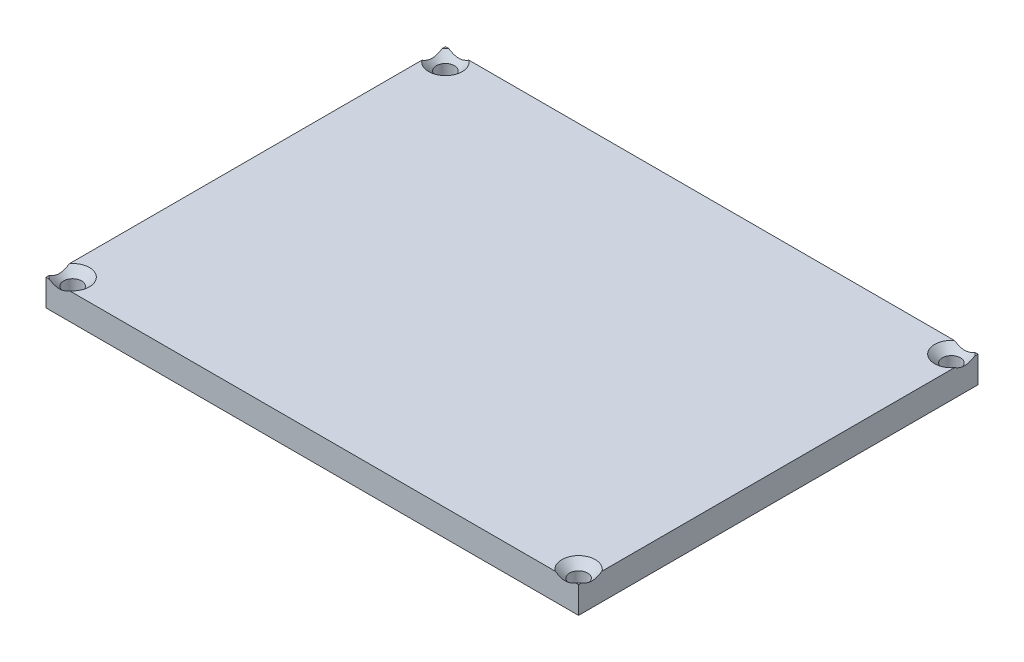
SolidWorks part; units mm, degrees
ref_plane "Alzado" through (0, 0, 0) normal (0, 0, 1) x (1, 0, 0)
ref_plane "Planta" through (0, 0, 0) normal (0, 1, 0) x (1, 0, 0)
ref_plane "Vista lateral" through (0, 0, 0) normal (1, 0, 0) x (0, 0, -1)
sketch "Croquis1" plane through (0, 0, 0) normal (0, 1, 0) x (1, 0, 0)
  line L1 (-67.5839, 18.7136) -> (32.4161, 18.7136)
  line L2 (-67.5839, 18.7136) -> (-67.5839, -56.2864)
  line L3 (-67.5839, -56.2864) -> (32.4161, -56.2864)
  line L4 (32.4161, 18.7136) -> (32.4161, -56.2864)
  dimension "D1" = 100
  dimension "D2" = 75
extrude "Saliente-Extruir1" add sketch "Croquis1" along normal blind 5
sketch "Croquis2" plane through (0, 0, 0) normal (0, 1, 0) x (1, 0, 0)
  line L0 (-67.5839, 18.7136) -> (-67.5839, -56.2864) construction
  line L1 (32.4161, 18.7136) -> (-67.5839, 18.7136) construction
  line L2 (32.4161, -56.2864) -> (32.4161, 18.7136) construction
  line L3 (-67.5839, -56.2864) -> (32.4161, -56.2864) construction
  point P0 (-65.0839, 16.2136)
  point P1 (29.9161, 16.2136)
  point P2 (29.9161, -53.7864)
  point P3 (-65.0839, -53.7864)
  dimension "D1" = 2.5
  dimension "D2" = 2.5
  dimension "D3" = 2.5
  dimension "D4" = 2.5
  dimension "D5" = 2.5
  dimension "D6" = 2.5
  dimension "D7" = 2.5
  dimension "D8" = 2.5
hole_wizard "Avellanado para tornillo con cabeza plana avellanada de M31" positions "Croquis3D1" profile "Croquis3" countersink size "M3" standard "DIN"
sketch3d "Croquis3D1"
  line L0 (-67.5839, 5, -18.7136) -> (-67.5839, 5, 56.2864) construction
  line L1 (-67.5839, 5, 56.2864) -> (32.4161, 5, 56.2864) construction
  point P0 (-65.0839, 0, -16.2136)
  point P3 (29.9161, 0, -16.2136)
  point P6 (29.9161, 0, 53.7864)
  point P9 (-65.0839, 0, 53.7864)
  point P12 (-65.0839, 5, -16.2136)
  point P15 (29.9161, 5, -16.2136)
  point P17 (29.9161, 5, 53.7864)
  point P19 (-65.0839, 5, 53.7864)
  dimension "D1" = 2.5
  dimension "D2" = 2.5
  dimension "D3" = 2.5
  dimension "D4" = 2.5
sketch "Croquis3" plane through (-65.0839, 5, 53.7864) normal (1, 0, 0) x (0, 0, 1)
  line L0 (0, 0) -> (0, 5)
  line L1 (0, 5) -> (1.7, 5)
  line L2 (1.7, 5) -> (1.7, 1.45)
  line L3 (1.7, 1.45) -> (3.15, 0)
  line L5 (3.15, 0) -> (0, 0)
  line L6 (-1.7, 1.45) -> (-3.15, 0) construction
  line L11 (0, -6.35) -> (0, 107.95) construction
  dimension "Diámetro de taladro hasta el siguiente" = 3.4
  dimension "Profundidad de taladro hasta el siguiente" = 5
  dimension "Diámetro de avellanado cercano" = 6.3
  dimension "Ángulo de avellanado cercano" = 90
